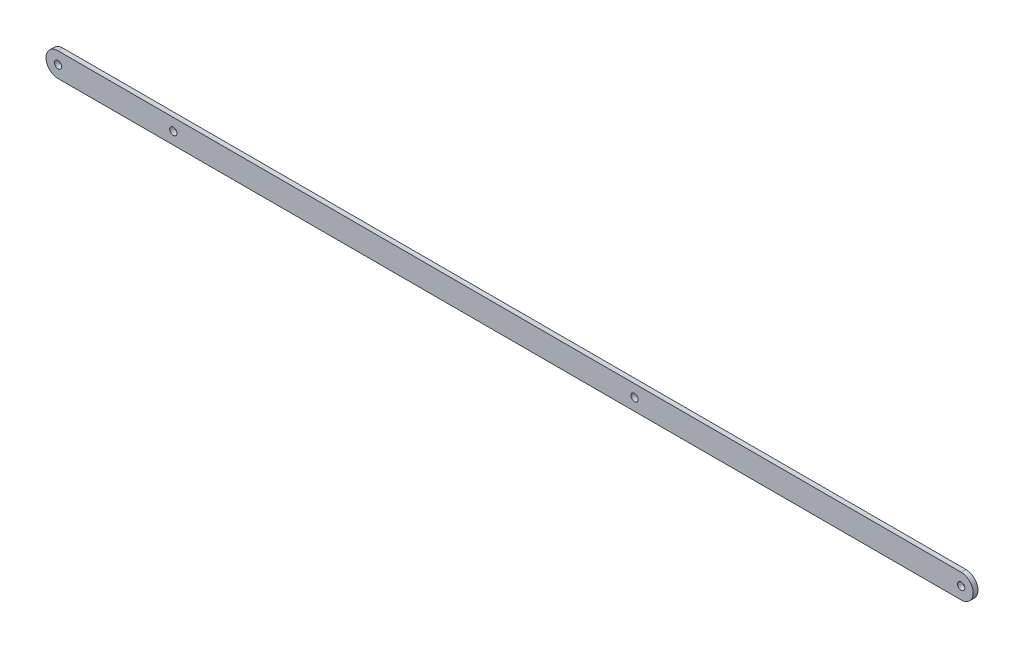
SolidWorks part; units mm, degrees
material "Plain Carbon Steel"
ref_plane "Front Plane" through (0, 0, 0) normal (0, 0, 1) x (1, 0, 0)
ref_plane "Top Plane" through (0, 0, 0) normal (0, 1, 0) x (1, 0, 0)
ref_plane "Right Plane" through (0, 0, 0) normal (1, 0, 0) x (0, 0, -1)
sketch "Sketch1" plane through (0, 0, 0) normal (0, 0, 1) x (1, 0, 0)
  line L0 (596.9, 0) -> (-596.9, 0) construction
  line L1 (3.4925, 0) -> (-3.4925, 0) construction
  line L2 (596.9, -15.875) -> (-596.9, -15.875)
  line L3 (596.9, 15.875) -> (-596.9, 15.875)
  arc A0 (596.9, -15.875) -> (596.9, 15.875) centre (596.9, 0) ccw
  arc A1 (-596.9, 15.875) -> (-596.9, -15.875) centre (-596.9, 0) ccw
  circle A2 centre (-596.9, 0) radius 4.7625
  circle A3 centre (596.9, 0) radius 4.7625
  point P5 (0, 0)
  dimension "D3" = 9.525
  dimension "D4" = 9.525
  dimension "D1" = 31.75
  dimension "D2" = 1193.8
extrude "Boss-Extrude1" add sketch "Sketch1" along normal mid plane 6.35
sketch "Sketch2" plane through (0, 0, 3.175) normal (0, 0, 1) x (1, 0, 0)
  line L0 (3.4925, 0) -> (-3.4925, 0) construction
  circle A0 centre (-444.5, 0) radius 4.7625
  circle A1 centre (-596.9, 0) radius 4.7625 construction
  circle A2 centre (165.1, 0) radius 4.7625
  circle A4 centre (596.9, 0) radius 4.7625 construction
  point P10 (0, 0)
  dimension "D1" = 152.4
  dimension "D2" = 431.8
extrude "Cut-Extrude1" cut sketch "Sketch2" against normal through all
sketch "Sketch3" plane through (0, 0, 3.175) normal (0, 0, 1) x (1, 0, 0)
  line L0 (-612.775, 0) -> (-612.775, 152.4)
  line L1 (-581.025, 152.4) -> (-581.025, 15.875)
  line L2 (596.9, 15.875) -> (-596.9, 15.875) construction
  line L3 (-581.025, 15.875) -> (-596.9, 15.875)
  arc A0 (-596.9, 15.875) -> (-596.9, -15.875) centre (-596.9, 0) ccw construction
  arc A1 (-612.775, 152.4) -> (-581.025, 152.4) centre (-596.9, 152.4) cw
  arc A2 (-596.9, 15.875) -> (-612.775, 0) centre (-596.9, 0) ccw
  circle A3 centre (-596.9, 0) radius 152.4 construction
  circle A4 centre (-596.9, 152.4) radius 4.7625
  dimension "D1" = 9.525
extrude "Boss-Extrude2" [suppressed] add sketch "Sketch3" against normal up to surface (6.35 mm away)
